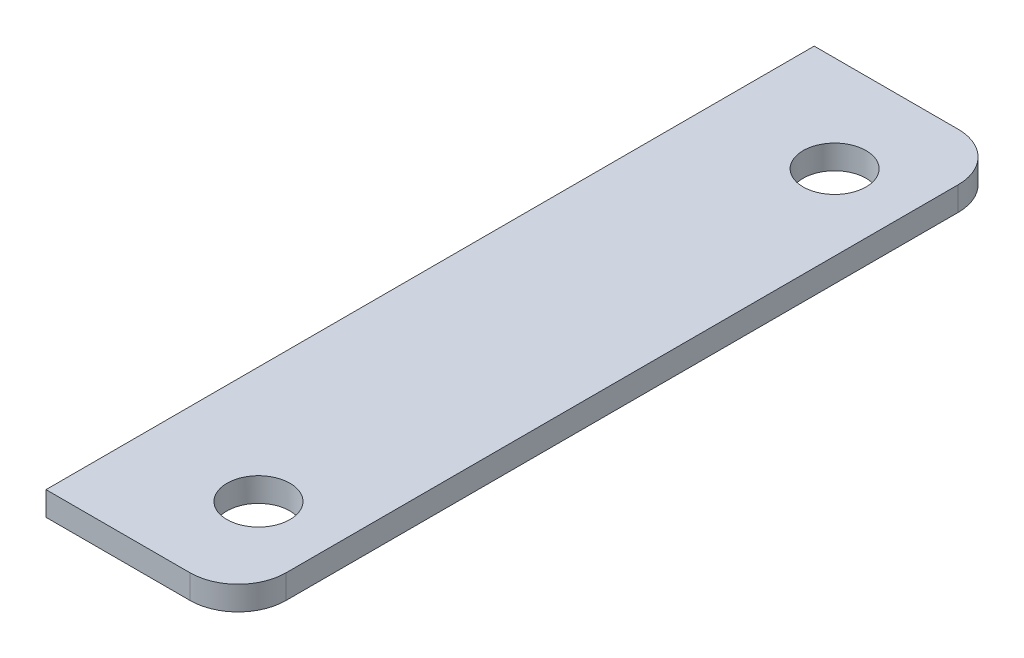
SolidWorks part; units mm, degrees
ref_plane "Front" through (0, 0, 0) normal (0, 0, 1) x (1, 0, 0)
ref_plane "Top" through (0, 0, 0) normal (0, 1, 0) x (1, 0, 0)
ref_plane "Right" through (0, 0, 0) normal (1, 0, 0) x (0, 0, -1)
sketch "Sketch1" plane through (0, 0, 0) normal (0, 1, 0) x (1, 0, 0)
  line L1 (-12.7, 50.8) -> (12.7, 50.8)
  line L2 (-12.7, 50.8) -> (-12.7, -50.8)
  line L3 (-12.7, -50.8) -> (12.7, -50.8)
  line L4 (12.7, 50.8) -> (12.7, -50.8)
  line L5 (-12.7, 50.8) -> (12.7, -50.8) construction
  line L6 (-12.7, -50.8) -> (12.7, 50.8) construction
  point P0 (0, 0)
  dimension "D1" = 101.6
  dimension "D2" = 25.4
extrude "Boss-Extrude1" add sketch "Sketch1" along normal blind 3.175
fillet "Fillet2" radius 6.35 2 edges at (12.7, 1.5875, 50.8) (12.7, 1.5875, -50.8)
sketch "Sketch2" plane through (0, 3.175, 0) normal (0, 1, 0) x (1, 0, 0)
  line L0 (2.7, 50.8) -> (2.7, -50.8) construction
  line L1 (6.35, 50.8) -> (-12.7, 50.8) construction
  line L2 (-12.7, -50.8) -> (6.35, -50.8) construction
  line L3 (-12.7, 0) -> (12.7, 0) construction
  line L4 (-12.7, 50.8) -> (-12.7, -50.8) construction
  line L5 (12.7, -44.45) -> (12.7, 44.45) construction
  circle A0 centre (2.7, 38.1) radius 4.165
  circle A1 centre (2.7, -38.1) radius 4.165
  dimension "D1" = 8.33
  dimension "D3" = 12.7
  dimension "D2" = 10
extrude "Cut-Extrude1" cut sketch "Sketch2" against normal up to next
